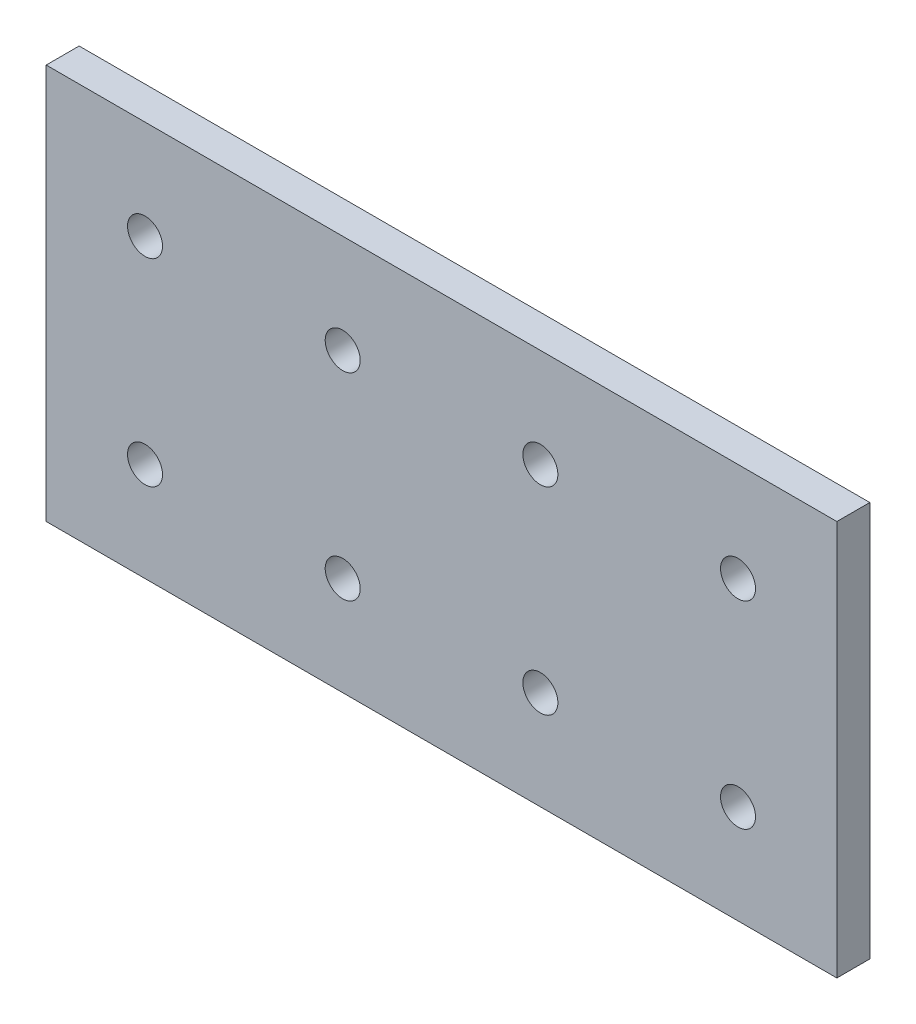
SolidWorks part; units mm, degrees
material "6061-T6 (SS)"
ref_plane "Front" through (0, 0, 0) normal (0, 0, 1) x (1, 0, 0)
ref_plane "Top" through (0, 0, 0) normal (0, 1, 0) x (1, 0, 0)
ref_plane "Right" through (0, 0, 0) normal (1, 0, 0) x (0, 0, -1)
sketch "Sketch1" plane through (0, 0, 0) normal (0, 0, 1) x (1, 0, 0)
  line L0 (0, 0) -> (152.4, 0)
  line L1 (152.4, 0) -> (152.4, 76.2)
  line L2 (152.4, 76.2) -> (0, 76.2)
  line L3 (0, 76.2) -> (0, 0)
  dimension "D1" = 152.4
  dimension "D2" = 76.2
extrude "Boss-Extrude1" add sketch "Sketch1" along normal blind 6.35
hole_wizard "17/64 (0.26563) Diameter Hole1" positions "Sketch2" profile "Sketch3" hole size "17/64" standard "ANSI Inch" end condition through all
sketch "Sketch2" plane through (0, 0, 6.35) normal (0, 0, 1) x (1, 0, 0)
  line L0 (0, 76.2) -> (0, 0) construction
  line L1 (0, 0) -> (152.4, 0) construction
  point P0 (19.05, 19.05)
  dimension "D1" = 19.05
  dimension "D2" = 19.05
sketch "Sketch3" plane through (19.05, 19.05, 6.35) normal (1, 0, 0) x (0, -1, 0)
  line L0 (0, 0) -> (0, 6.35)
  line L1 (0, 6.35) -> (3.3735, 6.35)
  line L2 (3.3735, 6.35) -> (3.3735, 0)
  line L5 (3.3735, 0) -> (0, 0)
  line L11 (0, -6.35) -> (0, 107.95) construction
  dimension "Thru Hole Dia." = 6.747
  dimension "Thru Hole Depth" = 6.35
pattern_linear "LPattern1" count 4 spacing 38.1 along (1, 0, 0) count 2 spacing 38.1 along (0, 1, 0) of "17/64 (0.26563) Diameter Hole1"
